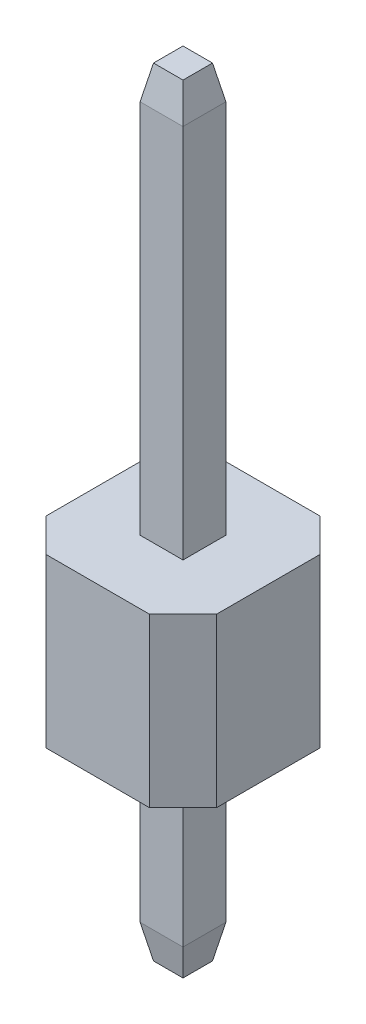
SolidWorks part; units mm, degrees
ref_plane "Спереди" through (0, 0, 0) normal (0, 0, 1) x (1, 0, 0)
ref_plane "Сверху" through (0, 0, 0) normal (0, 1, 0) x (1, 0, 0)
ref_plane "Справа" through (0, 0, 0) normal (1, 0, 0) x (0, 0, -1)
sketch "Эскиз1" plane through (0, 0, 0) normal (0, 1, 0) x (1, 0, 0)
  line L1 (-0.32, 0.32) -> (0.32, 0.32)
  line L2 (-0.32, 0.32) -> (-0.32, -0.32)
  line L3 (-0.32, -0.32) -> (0.32, -0.32)
  line L4 (0.32, 0.32) -> (0.32, -0.32)
  line L5 (-0.32, 0.32) -> (0.32, -0.32) construction
  line L6 (-0.32, -0.32) -> (0.32, 0.32) construction
  point P0 (0, 0)
  dimension "D1" = 0.64
  dimension "D2" = 0.64
extrude "Бобышка-Вытянуть1" add sketch "Эскиз1" against normal blind 3 and the other way blind 8.6
chamfer "Фаска1" distance 0.5 distance2 0.1 4 edges at (0, 8.6, 0.32) (-0.32, 8.6, 0) (0, 8.6, -0.32) (0.32, 8.6, 0)
chamfer "Фаска2" distance 0.1 distance2 0.5 4 edges at (0, -3, -0.32) (-0.32, -3, 0) (0, -3, 0.32) (0.32, -3, 0)
sketch "Эскиз2" plane through (0, 0, 0) normal (0, 1, 0) x (1, 0, 0)
  line L0 (-1.27, 0.77) -> (-0.77, 1.27)
  line L1 (-0.77, 1.27) -> (0.77, 1.27)
  line L2 (-1.27, 0.77) -> (-1.27, -0.77)
  line L3 (-0.77, -1.27) -> (0.77, -1.27)
  line L4 (1.27, 0.77) -> (1.27, -0.77)
  line L5 (-1.27, 1.27) -> (1.27, -1.27) construction
  line L6 (-1.27, -1.27) -> (1.27, 1.27) construction
  line L7 (0.77, 1.27) -> (1.27, 0.77)
  line L8 (0.77, -1.27) -> (1.27, -0.77)
  line L9 (-1.27, -0.77) -> (-0.77, -1.27)
  point P0 (0, 0)
  dimension "D1" = 2.54
  dimension "D2" = 2.54
extrude "Бобышка-Вытянуть2" add sketch "Эскиз2" along normal blind 2.5 separate body
